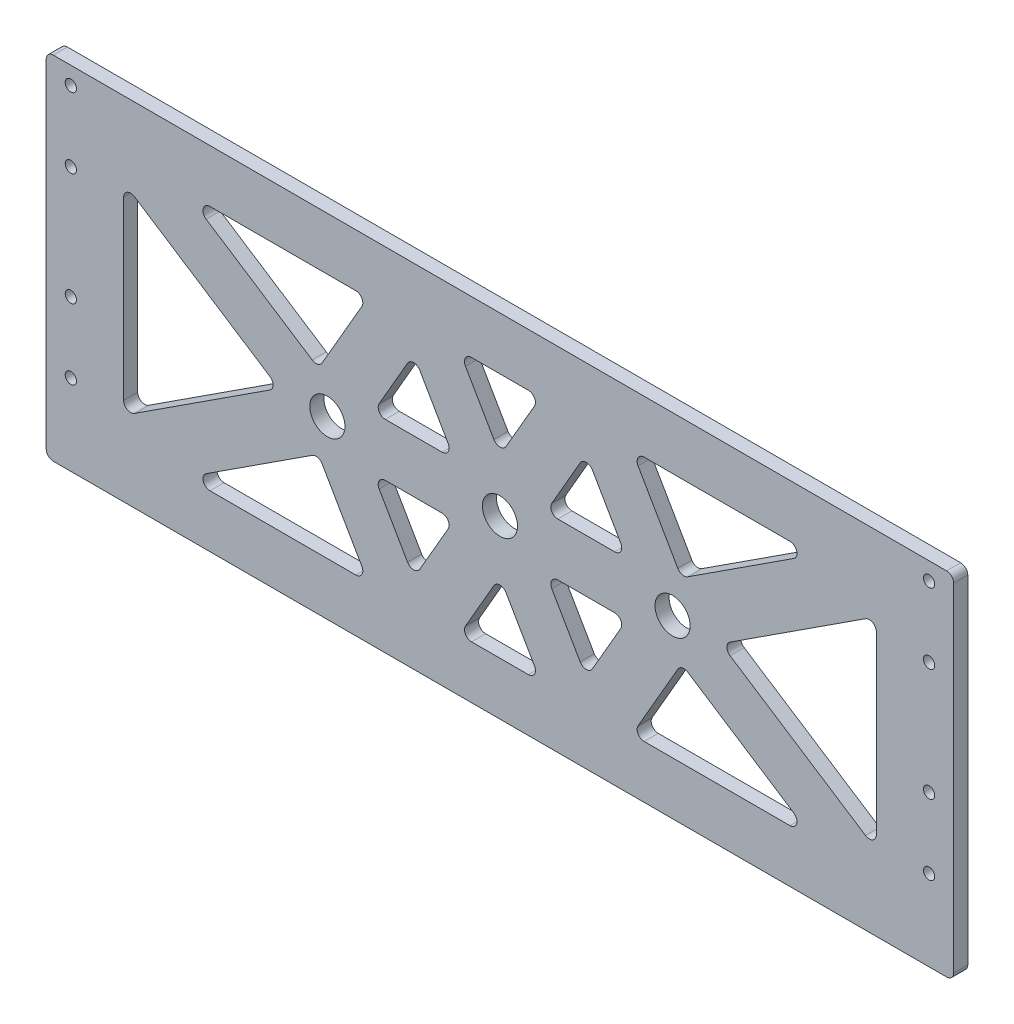
SolidWorks part; units mm, degrees
ref_plane "前视基准面" through (0, 0, 0) normal (0, 0, 1) x (1, 0, 0)
ref_plane "上视基准面" through (0, 0, 0) normal (0, 1, 0) x (1, 0, 0)
ref_plane "右视基准面" through (0, 0, 0) normal (1, 0, 0) x (0, 0, -1)
other "Configuration Table"
sketch "草图1" plane through (0, 0, 0) normal (0, 0, 1) x (1, 0, 0)
  line L1 (-129, -50) -> (129, -50)
  line L2 (-129, -50) -> (-129, 50)
  line L3 (-129, 50) -> (129, 50)
  line L4 (129, -50) -> (129, 50)
  line L5 (-129, -50) -> (129, 50) construction
  line L6 (-129, 50) -> (129, -50) construction
  point P0 (0, 0)
  dimension "D1" = 258
  dimension "D2" = 100
extrude "凸台-拉伸1" add sketch "草图1" along normal blind 4
fillet "圆角1" radius 2 4 edges at (129, -50, 2) (-129, -50, 2) (-129, 50, 2) (129, 50, 2)
sketch "草图2" plane through (0, 0, 0) normal (0, 0, -1) x (-1, 0, 0)
  circle A0 centre (-122, -27) radius 1.6
  circle A1 centre (-122, -7) radius 1.6
  circle A2 centre (-122, 25) radius 1.6
  circle A3 centre (-122, 45) radius 1.6
  circle A4 centre (122, -27) radius 1.6
  circle A5 centre (122, -7) radius 1.6
  circle A6 centre (122, 25) radius 1.6
  circle A7 centre (122, 45) radius 1.6
extrude "切除-拉伸1" cut sketch "草图2" against normal through all
sketch "草图3" plane through (0, 0, 4) normal (0, 0, 1) x (1, 0, 0)
  line L0 (127, 50) -> (-127, 50) construction
  line L1 (-24.5374, 42.5) -> (-49.0748, 0) construction
  line L2 (-49.0748, 0) -> (-24.5374, -42.5) construction
  line L3 (-24.5374, -42.5) -> (24.5374, -42.5) construction
  line L4 (24.5374, -42.5) -> (49.0748, 0) construction
  line L5 (49.0748, 0) -> (24.5374, 42.5) construction
  line L6 (24.5374, 42.5) -> (-24.5374, 42.5) construction
  line L7 (-24.5374, 42.5) -> (24.5374, -42.5) construction
  line L8 (24.5374, -42.5) -> (49.0748, 0) construction
  line L9 (49.0748, 0) -> (-49.0748, 0) construction
  line L10 (-24.5374, -42.5) -> (24.5374, 42.5) construction
  line L11 (-24.5374, 42.5) -> (-114.5, 42.5) construction
  line L12 (-114.5, 42.5) -> (-49.0748, 0) construction
  line L13 (-49.0748, 0) -> (-114.5, -42.5) construction
  line L14 (-114.5, -42.5) -> (-24.5374, -42.5) construction
  line L15 (-114.5, -42.5) -> (-114.5, 42.5) construction
  line L16 (24.5374, 42.5) -> (114.5, 42.5) construction
  line L17 (114.5, 42.5) -> (49.0748, 0) construction
  line L18 (49.0748, 0) -> (114.5, -42.5) construction
  line L19 (114.5, -42.5) -> (114.5, 42.5) construction
  line L20 (24.5374, -42.5) -> (114.5, -42.5) construction
  line L21 (-107, -42.5) -> (-107, 42.5)
  line L22 (-118.5856, 36.2105) -> (-53.1604, -6.2895)
  line L23 (-53.1604, 6.2895) -> (-118.5856, -36.2105)
  line L24 (-114.5, -50) -> (-24.5374, -50)
  line L25 (-24.5374, 50) -> (-114.5, 50)
  line L26 (-31.0326, 46.25) -> (-55.57, 3.75)
  line L27 (-55.57, -3.75) -> (-31.0326, -46.25)
  line L28 (-18.0422, -46.25) -> (31.0326, 38.75)
  line L29 (49.0748, 7.5) -> (-49.0748, 7.5)
  line L30 (-31.0326, 38.75) -> (18.0422, -46.25)
  line L31 (-24.5374, -50) -> (24.5374, -50)
  line L32 (24.5374, 50) -> (-24.5374, 50)
  line L33 (55.57, 3.75) -> (31.0326, 46.25)
  line L34 (31.0326, -46.25) -> (55.57, -3.75)
  line L35 (24.5374, -50) -> (114.5, -50)
  line L36 (44.9891, -6.2895) -> (110.4144, -48.7895)
  line L37 (110.4144, 48.7895) -> (44.9891, 6.2895)
  line L38 (24.5374, 35) -> (114.5, 35)
  line L39 (122, -42.5) -> (122, 42.5)
  line L40 (-122, -42.5) -> (-122, 42.5)
  line L41 (-112.3419, 50.0416) -> (-44.9891, 6.2895)
  line L42 (-44.9891, -6.2895) -> (-110.4144, -48.7895)
  line L43 (-114.5, -35) -> (-24.5374, -35)
  line L44 (-24.5374, 35) -> (-114.5, 35)
  line L45 (-18.0422, 38.75) -> (-42.5796, -3.75)
  line L46 (-42.5796, 3.75) -> (-18.0422, -38.75)
  line L47 (-31.0326, -38.75) -> (18.0422, 46.25)
  line L48 (49.0748, -7.5) -> (-49.0748, -7.5)
  line L49 (-18.0422, 46.25) -> (31.0326, -38.75)
  line L50 (-24.5374, -35) -> (24.5374, -35)
  line L51 (24.5374, 35) -> (-24.5374, 35)
  line L52 (42.5796, -3.75) -> (18.0422, 38.75)
  line L53 (18.0422, -38.75) -> (42.5796, 3.75)
  line L54 (24.5374, -35) -> (114.5, -35)
  line L55 (53.1604, 6.2895) -> (118.5856, -36.2105)
  line L56 (118.5856, 36.2105) -> (53.1604, -6.2895)
  line L57 (24.5374, 50) -> (114.5, 50)
  line L58 (107, -42.5) -> (107, 42.5)
  line L59 (-110.4144, 48.7895) -> (-44.9891, 6.2895) construction
  circle A0 centre (0, 0) radius 42.5 construction
  circle A1 centre (-122, 25) radius 1.6 construction
  circle A2 centre (122, -7) radius 1.6 construction
  circle A3 centre (-49.0748, 0) radius 5
  circle A4 centre (49.0748, 0) radius 5
  dimension "D6" = 10
  dimension "D7" = 10
  dimension "D1" = 7.5
  dimension "D2" = 7.5
  dimension "D3" = 7.5
  dimension "D4" = 7.5
  dimension "D5" = 7.5
extrude "切除-拉伸2" cut sketch "草图3" against normal through all contours L23 L22 L21 | L30 L45 L29 | L26 L44 L41 | L42 L43 L27 | L47 L48 L46 | L28 L50 L30 | L47 L51 L49 | L49 L53 L48 | L38 L33 L37 | L55 L58 L56 | L34 L54 L36 | L29 L52 L28 | A3 | A4
fillet "圆角2" radius 2 36 edges at (107, -28.6845, 2) (107, 28.6845, 2) (62.8425, 0, 2) (51.6178, 10.5954, 2) (37.5278, 35, 2) (89.1866, 35, 2) (89.1866, -35, 2) (51.6178, -10.5954, 2) (37.5278, -35, 2) (24.5374, -27.5, 2) (12.9904, -7.5, 2) (36.0844, -7.5, 2) (36.0844, 7.5, 2) (12.9904, 7.5, 2) (24.5374, 27.5, 2) (-11.547, 35, 2) (11.547, 35, 2) (0, 15, 2) (0, -15, 2) (11.547, -35, 2) (-11.547, -35, 2) (-24.5374, -27.5, 2) (-12.9904, -7.5, 2) (-36.0844, -7.5, 2) (-36.0844, 7.5, 2) (-12.9904, 7.5, 2) (-24.5374, 27.5, 2) (-89.1866, 35, 2) (-37.5278, 35, 2) (-51.6178, 10.5954, 2) (-89.1866, -35, 2) (-37.5278, -35, 2) (-51.6178, -10.5954, 2) (-107, -28.6845, 2) (-62.8425, 0, 2) (-107, 28.6845, 2)
sketch "草图4" plane through (0, 0, 4) normal (0, 0, 1) x (1, 0, 0)
  circle A0 centre (0, 0) radius 5
  dimension "D1" = 10
extrude "切除-拉伸3" cut sketch "草图4" against normal through all
